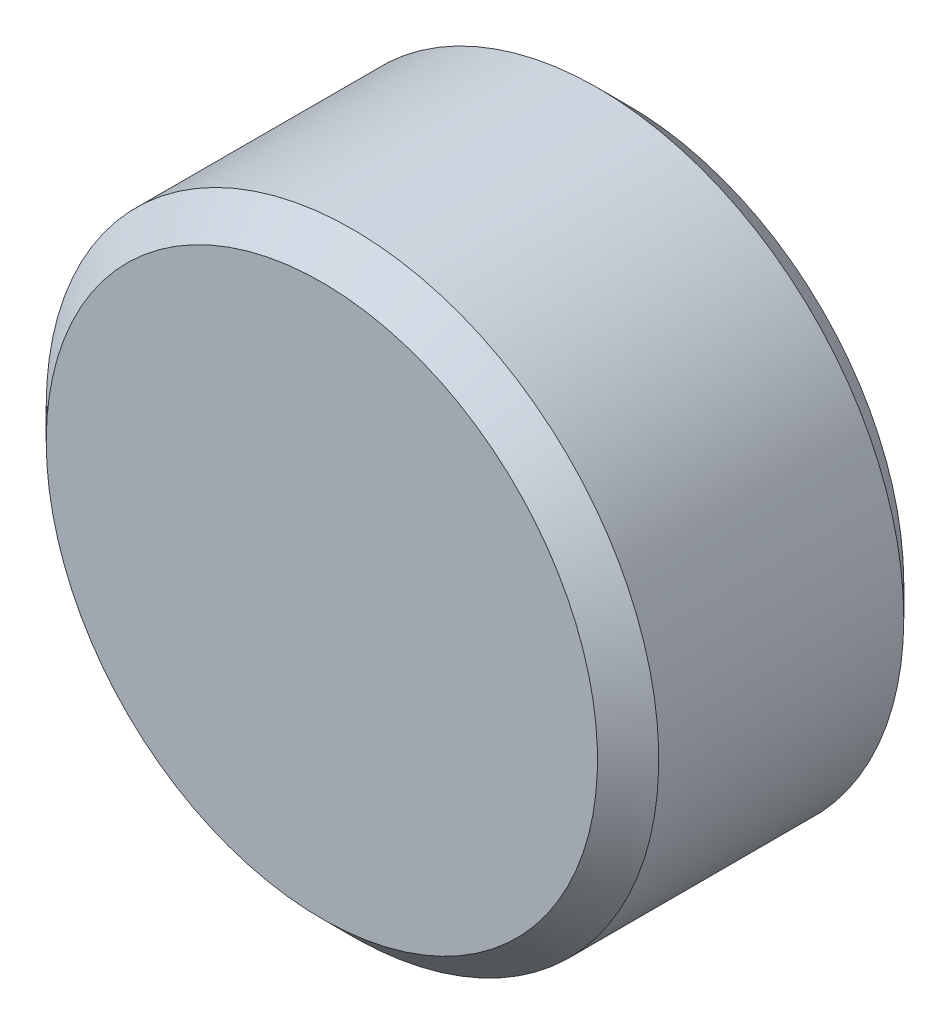
SolidWorks part; units mm, degrees
ref_plane "Front" through (0, 0, 0) normal (0, 0, 1) x (1, 0, 0)
ref_plane "Top" through (0, 0, 0) normal (0, 1, 0) x (1, 0, 0)
ref_plane "Right" through (0, 0, 0) normal (1, 0, 0) x (0, 0, -1)
sketch "Эскиз1" plane through (0, 0, 0) normal (0, 0, 1) x (1, 0, 0)
  circle A0 centre (0, 0) radius 3
  dimension "D1" = 6
extrude "Бобышка-Вытянуть1" add sketch "Эскиз1" along normal blind 3
chamfer "Фаска1" distance 0.3 angle 45 2 edges at (3, 0, 3) (3, 0, 0)
